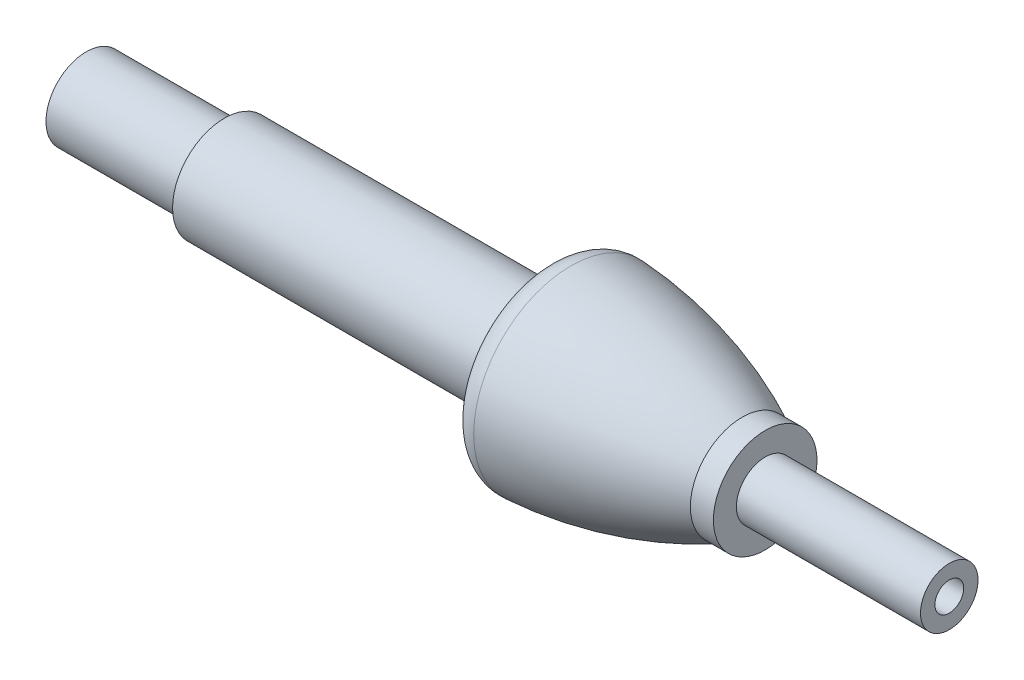
SolidWorks part; units mm, degrees
ref_plane "Alzado" through (0, 0, 0) normal (0, 0, 1) x (1, 0, 0)
ref_plane "Planta" through (0, 0, 0) normal (0, 1, 0) x (1, 0, 0)
ref_plane "Vista lateral" through (0, 0, 0) normal (1, 0, 0) x (0, 0, -1)
sketch "Croquis1" plane through (0, 0, 0) normal (0, 0, 1) x (1, 0, 0)
  line L0 (-37.5, 0) -> (37.5, 0)
  line L1 (-37.5, 0) -> (-37.5, 3.5)
  line L2 (-37.5, 3.5) -> (-25.5, 3.5)
  line L3 (-25.5, 3.5) -> (-25.5, 4.5)
  line L4 (-25.5, 4.5) -> (2.5, 4.5)
  line L5 (2.5, 4.5) -> (2.5, 8.5)
  line L6 (19.5, 4.5) -> (21.5, 4.5)
  line L7 (21.5, 4.5) -> (21.5, 2.5)
  line L8 (21.5, 2.5) -> (37.5, 2.5)
  line L9 (37.5, 2.5) -> (37.5, 0)
  arc A0 (2.5, 8.5) -> (19.5, 4.5) centre (2.5, -29.625) cw
  point P4 (0, 0)
  point P15 (0, 0)
  dimension "D1" = 75
  dimension "D2" = 8.5
  dimension "D3" = 4.5
  dimension "D4" = 3.5
  dimension "D5" = 12
  dimension "D6" = 40
  dimension "D7" = 16
  dimension "D8" = 2.5
  dimension "D9" = 2
revolve "Revolución1" add sketch "Croquis1" angle 360 about L0
fillet "Redondeo1" radius 2 1 edges at (2.5, 0, 8.5)
sketch "Croquis2" plane through (37.5, 0, 0) normal (1, 0, 0) x (0, 0, -1)
  circle A0 centre (0, 0) radius 1.25
  dimension "D1" = 2.5
extrude "Cortar-Extruir1" cut sketch "Croquis2" against normal through all
